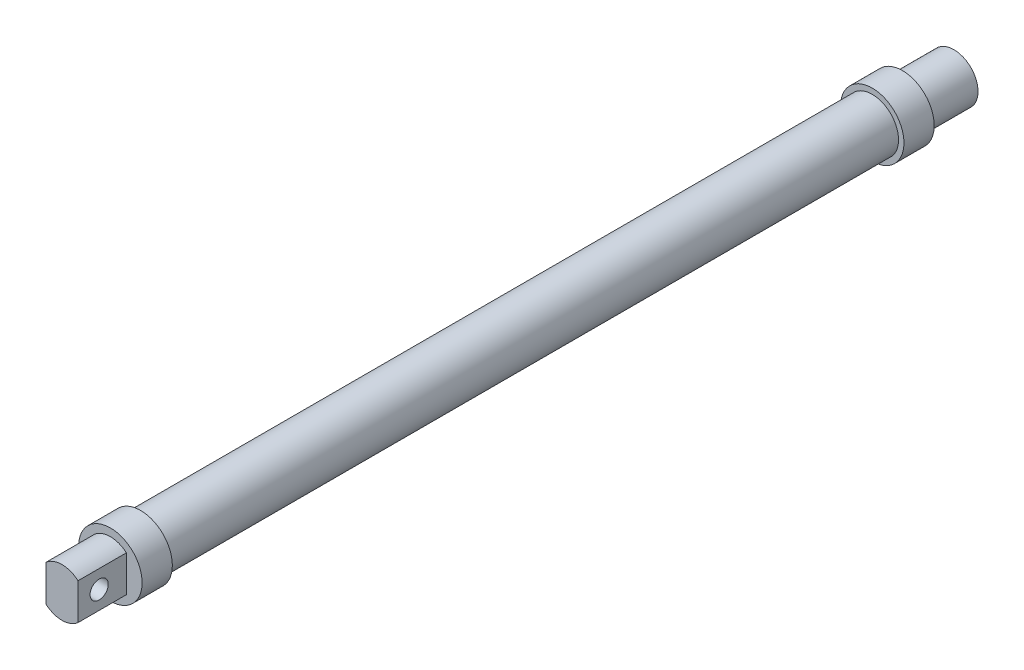
SolidWorks part; units mm, degrees
ref_plane "Front Plane" through (0, 0, 0) normal (0, 0, 1) x (1, 0, 0)
ref_plane "Top Plane" through (0, 0, 0) normal (0, 1, 0) x (1, 0, 0)
ref_plane "Right Plane" through (0, 0, 0) normal (1, 0, 0) x (0, 0, -1)
sketch "Sketch1" plane through (0, 0, 0) normal (0, 0, 1) x (1, 0, 0)
  circle A0 centre (0, 0) radius 10.5
extrude "Boss-Extrude1" add sketch "Sketch1" along normal blind 10
sketch "Sketch2" plane through (0, 0, 10) normal (0, 0, 1) x (1, 0, 0)
  line L1 (-5.2915, -6) -> (5.2915, -6)
  line L2 (-5.2915, -6) -> (-5.2915, 6)
  line L3 (-5.2915, 6) -> (5.2915, 6)
  line L4 (5.2915, -6) -> (5.2915, 6)
  line L5 (-5.2915, -6) -> (5.2915, 6) construction
  line L6 (-5.2915, 6) -> (5.2915, -6) construction
  circle A0 centre (0, 0) radius 8
  dimension "D1" = 16
  dimension "D2" = 12
extrude "Boss-Extrude2" add sketch "Sketch2" along normal blind 16 contours L1 L4 L3 L2 | L3 A0 | L1 A0
sketch "Sketch3" plane through (5.2915, 0, 0) normal (1, 0, 0) x (0, 0, -1)
  line L0 (-26, -6) -> (-10, -6) construction
  line L1 (-10, -6) -> (-10, 6) construction
  circle A0 centre (-19, 0) radius 3
  dimension "D1" = 6
  dimension "D2" = 9
extrude "Cut-Extrude1" cut sketch "Sketch3" against normal up to next
sketch "Sketch4" plane through (0, 0, 0) normal (0, 0, -1) x (-1, 0, 0)
  circle A0 centre (0, 0) radius 8.7
  dimension "D1" = 17.4
extrude "Boss-Extrude3" add sketch "Sketch4" along normal blind 242
sketch "Sketch5" plane through (0, 0, -242) normal (0, 0, -1) x (-1, 0, 0)
  circle A0 centre (0, 0) radius 10.5
  dimension "D1" = 21
extrude "Boss-Extrude4" add sketch "Sketch5" along normal blind 10
sketch "Sketch6" plane through (0, 0, -252) normal (0, 0, -1) x (-1, 0, 0)
  circle A0 centre (0, 0) radius 8
  dimension "D1" = 16
extrude "Boss-Extrude5" add sketch "Sketch6" along normal blind 17
sketch "Sketch7" plane through (0, 0, -269) normal (0, 0, -1) x (-1, 0, 0)
  circle A0 centre (0, 0) radius 3
  dimension "D1" = 6
extrude "Cut-Extrude2" cut sketch "Sketch7" against normal blind 201
sketch "Sketch8" plane through (-5.2915, 0, 0) normal (-1, 0, 0) x (0, 0, 1)
  line L0 (10, 0) -> (26, 0)
  line L1 (10, -6) -> (10, 6) construction
  line L2 (26, -6) -> (26, 6) construction
